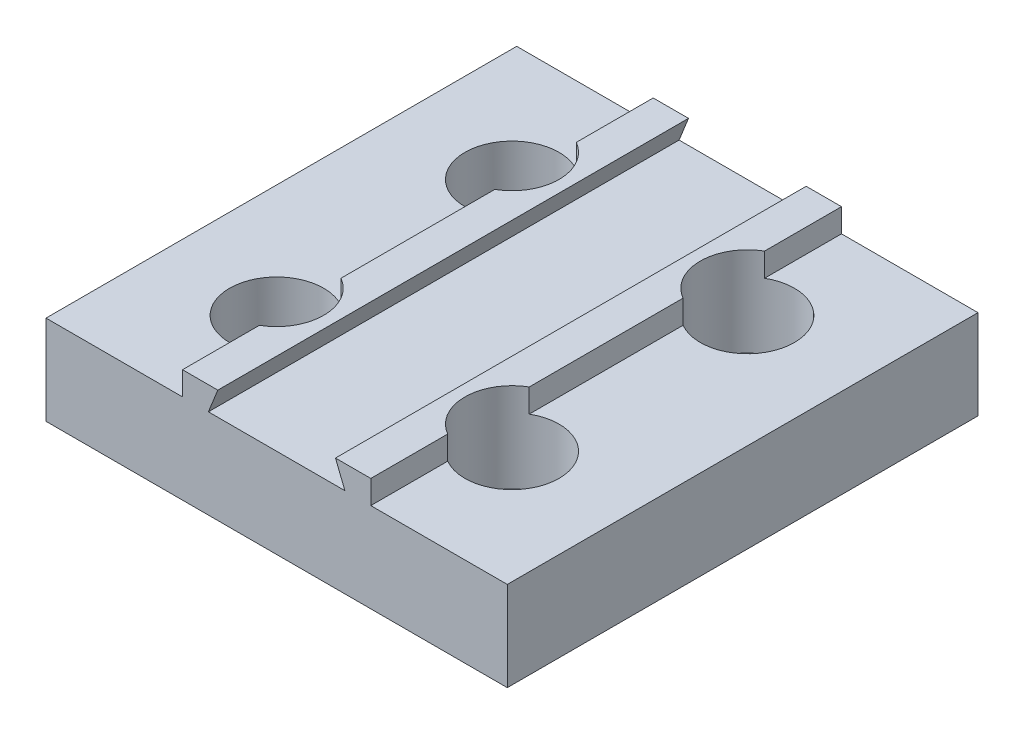
SolidWorks part; units mm, degrees
ref_plane "Front Plane" through (0, 0, 0) normal (0, 0, 1) x (1, 0, 0)
ref_plane "Top Plane" through (0, 0, 0) normal (0, 1, 0) x (1, 0, 0)
ref_plane "Right Plane" through (0, 0, 0) normal (1, 0, 0) x (0, 0, -1)
sketch "Sketch1" plane through (0, 0, 0) normal (0, 1, 0) x (1, 0, 0)
  line L1 (-10, -25) -> (10, -25)
  line L2 (-10, -25) -> (-10, 25)
  line L3 (-10, 25) -> (10, 25)
  line L4 (10, -25) -> (10, 25)
  line L5 (-10, -25) -> (10, 25) construction
  line L6 (-10, 25) -> (10, -25) construction
  point P0 (0, 0)
extrude "Boss-Extrude1" add sketch "Sketch1" along normal blind 12
sketch "Sketch2" plane through (0, 0, 25) normal (0, 0, 1) x (1, 0, 0)
  line L0 (0, 12) -> (0, 9.5) construction
  line L8 (-10, 12) -> (10, 12) construction
  line L9 (0, 9.5) -> (7.25, 9.5)
  line L10 (0, 9.5) -> (-7.25, 9.5)
  line L11 (0, 12) -> (6.25, 12)
  line L12 (0, 12) -> (-6.25, 12)
  line L13 (-7.25, 9.5) -> (-6.25, 12)
  line L14 (6.25, 12) -> (7.25, 9.5)
extrude "Cut-Extrude1" cut sketch "Sketch2" against normal up to next
sketch "Sketch4" plane through (-10, 0, 0) normal (-1, 0, 0) x (0, 0, 1)
  line L1 (-25, 9.5) -> (25, 9.5)
  line L2 (-25, 9.5) -> (-25, 0)
  line L3 (-25, 0) -> (25, 0)
  line L4 (25, 9.5) -> (25, 0)
extrude "Boss-Extrude2" add sketch "Sketch4" along normal blind 14.5
sketch "Sketch5" plane through (10, 0, 0) normal (1, 0, 0) x (0, 0, -1)
  line L1 (25, 9.5) -> (-25, 9.5)
  line L2 (25, 9.5) -> (25, 0)
  line L3 (25, 0) -> (-25, 0)
  line L4 (-25, 9.5) -> (-25, 0)
extrude "Boss-Extrude3" add sketch "Sketch5" along normal blind 14.5
sketch "Sketch10" plane through (0, 9.5, 0) normal (0, 1, 0) x (1, 0, 0)
  line L0 (0, -25) -> (12.5, -25) construction
  line L1 (-7.25, -25) -> (7.25, -25) construction
  line L2 (24.5, -25) -> (10, -25) construction
  line L3 (12.5, -25) -> (12.5, -12.5) construction
  line L4 (12.5, -12.5) -> (-12.5, -12.5) construction
  line L5 (12.5, -12.5) -> (12.5, 12.5) construction
  line L6 (12.5, 12.5) -> (-12.5, 12.5) construction
  circle A0 centre (-12.5, 12.5) radius 5
  circle A1 centre (12.5, 12.5) radius 5
  circle A2 centre (-12.5, -12.5) radius 5
  circle A3 centre (12.5, -12.5) radius 5
extrude "Cut-Extrude4" cut sketch "Sketch10" against normal blind 7 and the other way up to next
sketch "Sketch11" plane through (0, 2.5, 0) normal (0, 1, 0) x (1, 0, 0)
  circle A0 centre (-12.5, 12.5) radius 2.25
  circle A1 centre (12.5, 12.5) radius 2.25
  circle A2 centre (-12.5, -12.5) radius 2.25
  circle A3 centre (12.5, -12.5) radius 2.25
extrude "Cut-Extrude5" cut sketch "Sketch11" against normal up to next
